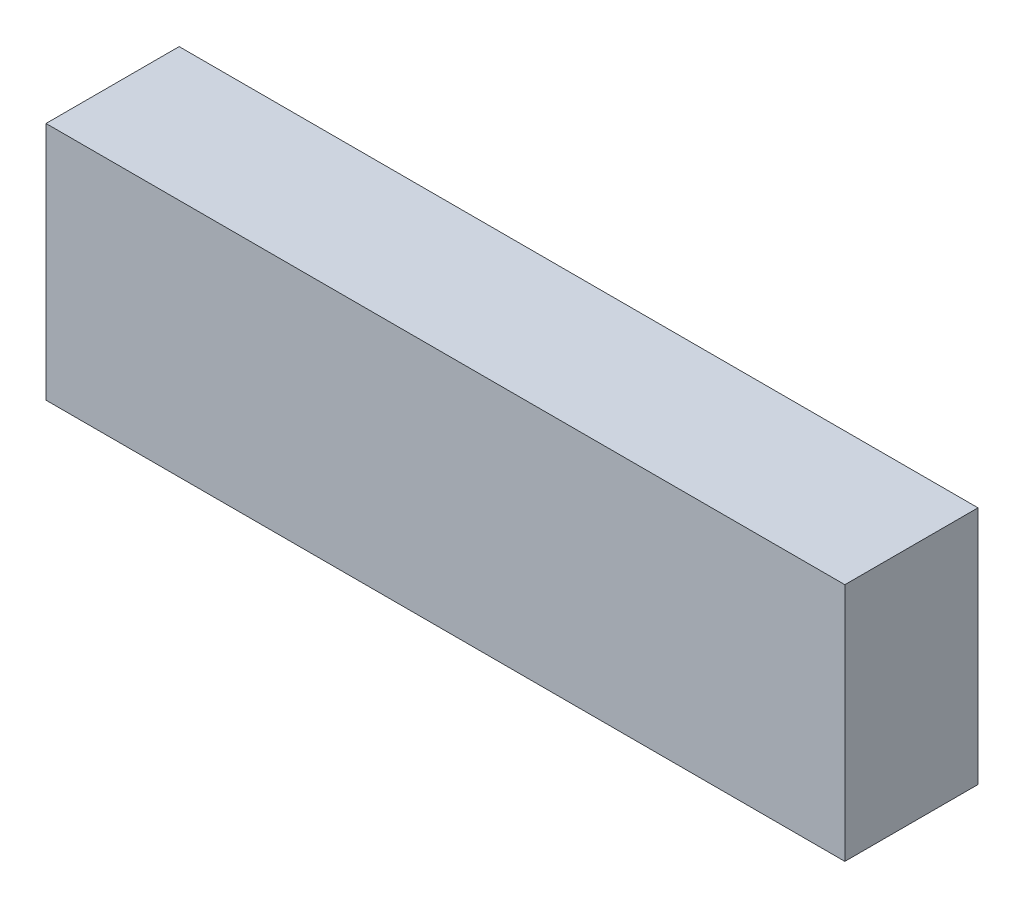
SolidWorks part; units mm, degrees
material "Silicon Dioxide"
ref_plane "Front Plane" through (0, 0, 0) normal (0, 0, 1) x (1, 0, 0)
ref_plane "Top Plane" through (0, 0, 0) normal (0, 1, 0) x (1, 0, 0)
ref_plane "Right Plane" through (0, 0, 0) normal (1, 0, 0) x (0, 0, -1)
sketch "Sketch1" plane through (0, 0, 0) normal (0, 0, 1) x (1, 0, 0)
  line L1 (-75.6362, 48.0134) -> (104.3638, 48.0134)
  line L2 (-75.6362, 48.0134) -> (-75.6362, -5.9866)
  line L3 (-75.6362, -5.9866) -> (104.3638, -5.9866)
  line L4 (104.3638, 48.0134) -> (104.3638, -5.9866)
  dimension "D1" = 180
  dimension "D2" = 54
extrude "Boss-Extrude1" add sketch "Sketch1" along normal blind 30
